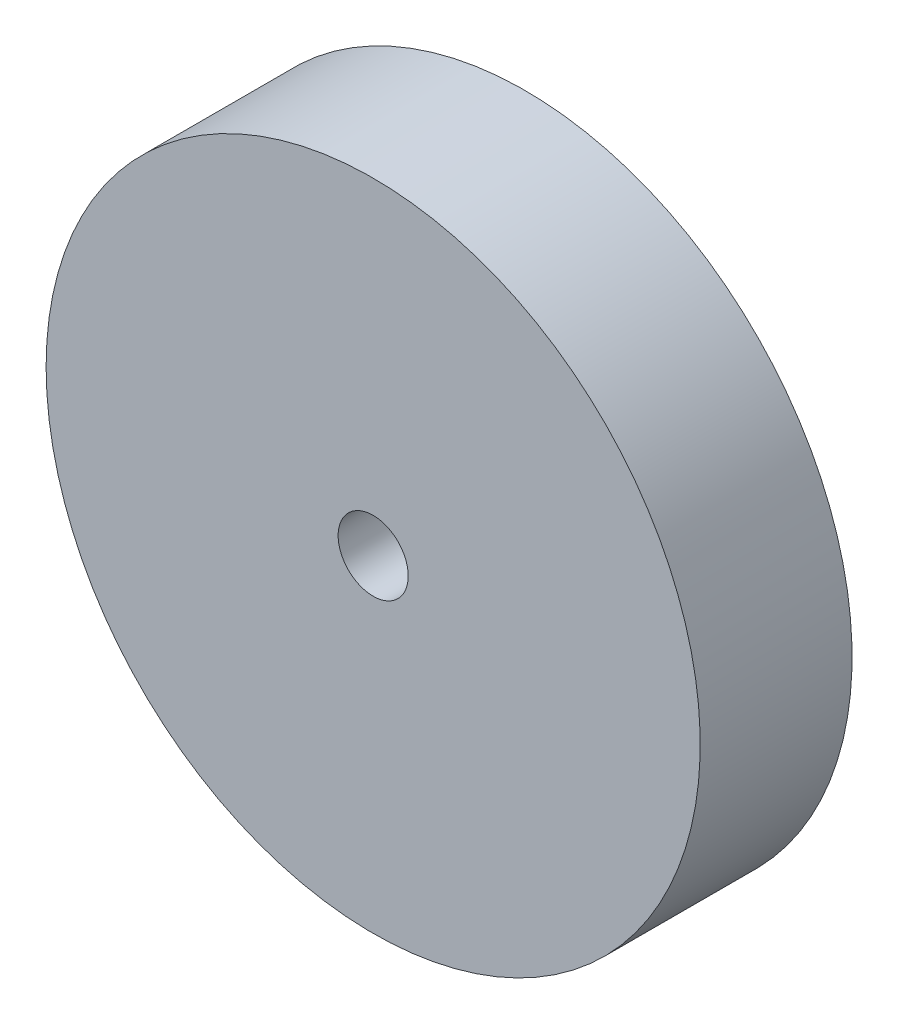
SolidWorks part; units mm, degrees
ref_plane "Front" through (0, 0, 0) normal (0, 0, 1) x (1, 0, 0)
ref_plane "Top" through (0, 0, 0) normal (0, 1, 0) x (1, 0, 0)
ref_plane "Right" through (0, 0, 0) normal (1, 0, 0) x (0, 0, -1)
sketch "Esquisse1" plane through (0, 0, 0) normal (0, 0, 1) x (1, 0, 0)
  circle A0 centre (0, 0) radius 28
  dimension "D1" = 56
extrude "Boss.-Extru.1" add sketch "Esquisse1" along normal blind 13
sketch "Esquisse2" plane through (0, 0, 13) normal (0, 0, 1) x (1, 0, 0)
  circle A0 centre (0, 0) radius 3
  dimension "D1" = 6
extrude "Enlèv. mat.-Extru.1" cut sketch "Esquisse2" against normal through all
